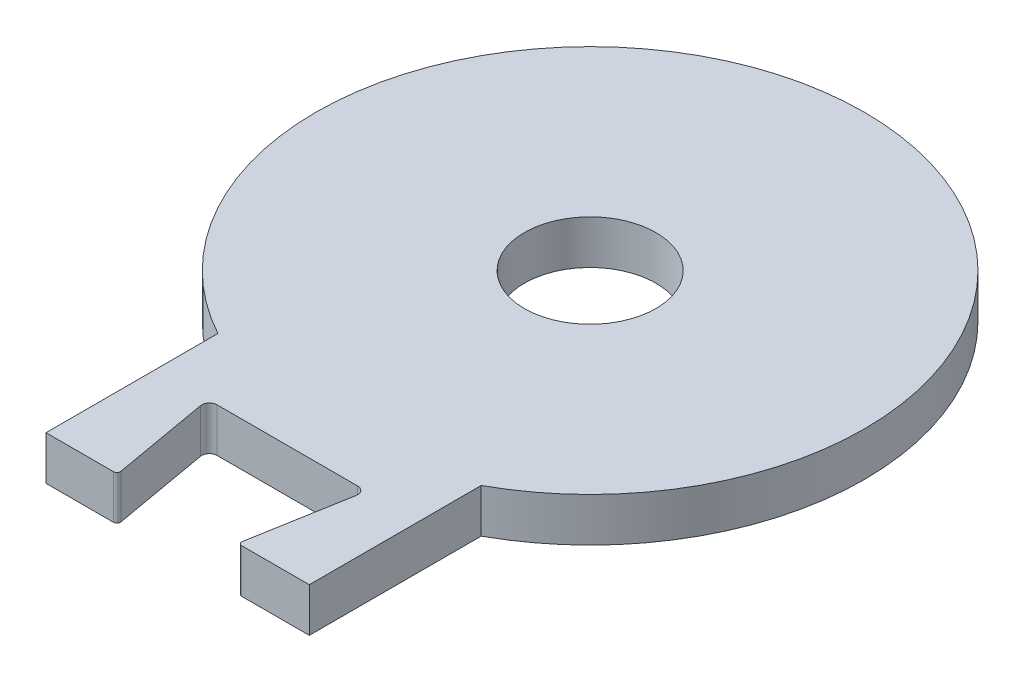
SolidWorks part; units mm, degrees
ref_plane "Front Plane" through (0, 0, 0) normal (0, 0, 1) x (1, 0, 0)
ref_plane "Top Plane" through (0, 0, 0) normal (0, 1, 0) x (1, 0, 0)
ref_plane "Right Plane" through (0, 0, 0) normal (1, 0, 0) x (0, 0, -1)
sketch "Sketch1" plane through (0, 0, 0) normal (0, 1, 0) x (1, 0, 0)
  line L0 (-6, 6) -> (-6, -13.2915)
  line L1 (-6, -19) -> (-2.7023, -19)
  line L2 (6, -19) -> (6, -13.2915)
  line L3 (6, 6) -> (-6, 6)
  line L4 (-6, -13.2915) -> (-6, -19)
  line L5 (6, -13.2915) -> (6, 6)
  line L6 (0, -19) -> (0, 0) construction
  line L7 (-2.6007, -19) -> (-3.5, -13.9) construction
  line L8 (-3.5, -13.9) -> (0, -13.9) construction
  line L9 (-2.7023, -19) -> (-3.6192, -13.8)
  line L10 (-3.6192, -13.8) -> (0, -13.8)
  line L11 (-2.6992, -19.0174) -> (-3.6192, -13.8) construction
  line L12 (2.7023, -19) -> (6, -19)
  line L13 (3.6192, -13.8) -> (0, -13.8)
  line L14 (2.7023, -19) -> (3.6192, -13.8)
  circle A0 centre (0, 0) radius 3
  dimension "D1" = 6
  dimension "D5" = 6
  dimension "D7" = 80
  dimension "D2" = 25
  dimension "D3" = 6
  dimension "D4" = 12
  dimension "D8" = 3.5
  dimension "D9" = 5.1
  dimension "D10" = 0.1
extrude "Boss-Extrude1" add sketch "Sketch1" along normal blind 2
sketch "Sketch2" plane through (0, 0, 0) normal (0, 1, 0) x (1, 0, 0)
  circle A0 centre (0, 0) radius 12.5
  circle A1 centre (0, 0) radius 3
  dimension "D1" = 25
extrude "Boss-Extrude2" add sketch "Sketch2" along normal blind 2
sketch "Sketch3" plane through (0, 0, 0) normal (0, -1, 0) x (1, 0, 0)
  line L0 (-3, 0) -> (-3, 4)
  line L1 (3, 0) -> (3, 4)
  arc A0 (-3, 0) -> (3, 0) centre (0, 0) ccw
  arc A1 (-3, 4) -> (3, 4) centre (0, 0) ccw
extrude "Boss-Extrude3" [suppressed] add sketch "Sketch3" along normal blind 4
fillet "Fillet1" [suppressed] radius 0.5
fillet "Fillet2" [suppressed] radius 1
sketch "Sketch4" plane through (0, 2, 0) normal (0, 1, 0) x (1, 0, 0)
  line L0 (-6, -10.9659) -> (-6, -19) construction
  line L1 (-6, -18.8) -> (6, -18.8)
  line L2 (-6, -18.8) -> (-6, -19)
  line L3 (-6, -19) -> (6, -19)
  line L4 (6, -18.8) -> (6, -19)
  dimension "D1" = 0.2
extrude "Cut-Extrude1" cut sketch "Sketch4" against normal blind 4
fillet "Fillet3" radius 0.35 2 edges at (3.6192, 1, 13.8) (-3.6192, 1, 13.8)
fillet "Fillet4" radius 0.15 2 edges at (2.7375, 1, 18.8) (-2.7375, 1, 18.8)
